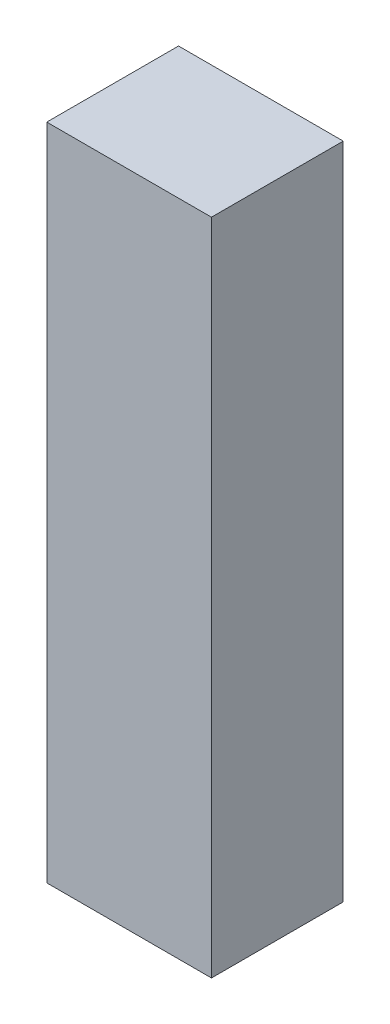
SolidWorks part; units mm, degrees
ref_plane "Front Plane" through (0, 0, 0) normal (0, 0, 1) x (1, 0, 0)
ref_plane "Top Plane" through (0, 0, 0) normal (0, 1, 0) x (1, 0, 0)
ref_plane "Right Plane" through (0, 0, 0) normal (1, 0, 0) x (0, 0, -1)
other "Configuration Table"
sketch "Sketch1" plane through (0, 0, 0) normal (0, 0, 1) x (1, 0, 0)
  line L1 (200, 330) -> (250, 330)
  line L2 (200, 330) -> (200, 530)
  line L3 (200, 530) -> (250, 530)
  line L4 (250, 330) -> (250, 530)
extrude "TOPPING_arka_duvar_pano_surucu_2_1" add sketch "Sketch1" against normal blind 40 from offset 736 separate body
